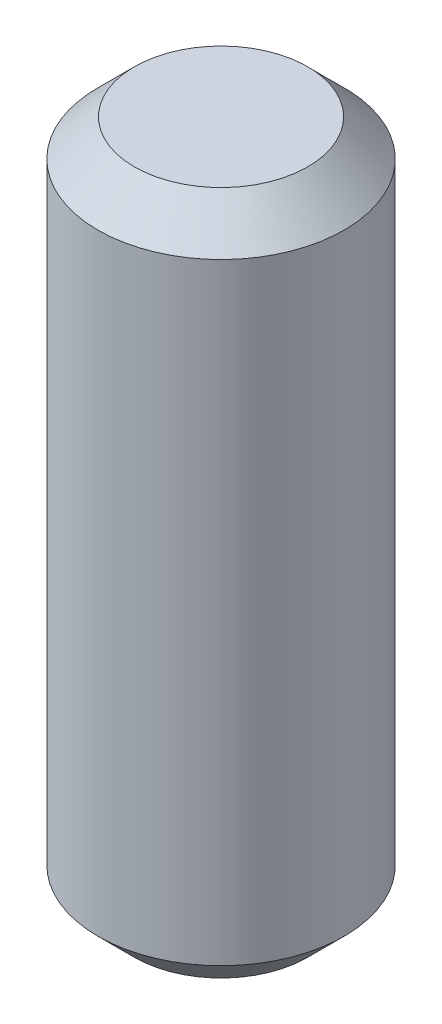
SolidWorks part; units mm, degrees
ref_plane "Front Plane" through (0, 0, 0) normal (0, 0, 1) x (1, 0, 0)
ref_plane "Top Plane" through (0, 0, 0) normal (0, 1, 0) x (1, 0, 0)
ref_plane "Right Plane" through (0, 0, 0) normal (1, 0, 0) x (0, 0, -1)
sketch "Sketch1" plane through (0, 0, 0) normal (0, 1, 0) x (1, 0, 0)
  circle A0 centre (0, 0) radius 2.7
  dimension "D1" = 5.4
extrude "Boss-Extrude1" add sketch "Sketch1" along normal blind 15
chamfer "Chamfer1" distance 0.8 2 edges at (0, 0, 2.7) (0, 15, 2.7)
